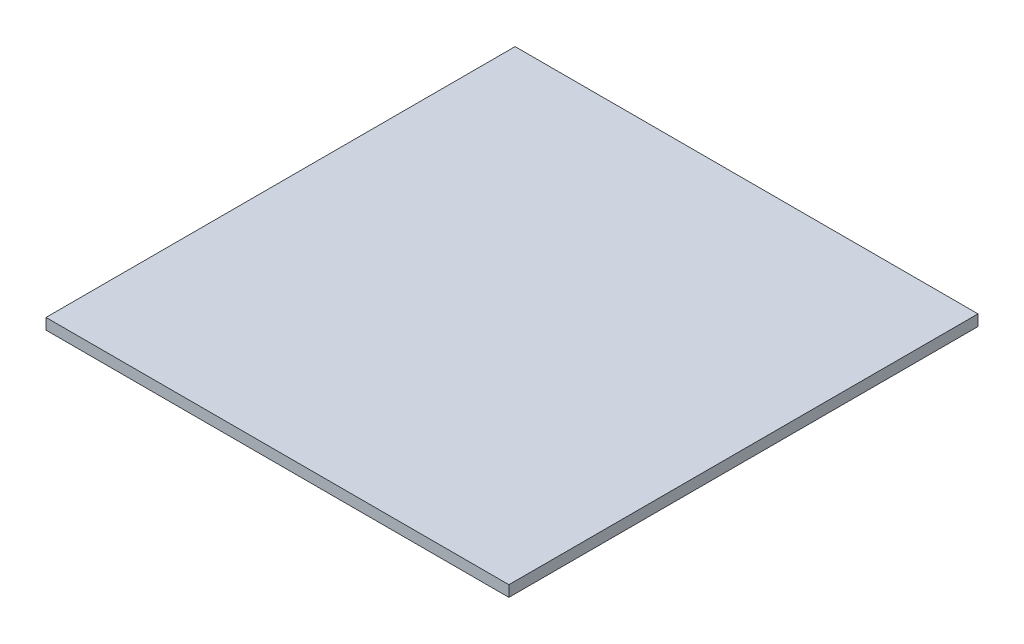
SolidWorks part; units mm, degrees
ref_plane "Plan de face" through (0, 0, 0) normal (0, 0, 1) x (1, 0, 0)
ref_plane "Plan de dessus" through (0, 0, 0) normal (0, 1, 0) x (1, 0, 0)
ref_plane "Plan de droite" through (0, 0, 0) normal (1, 0, 0) x (0, 0, -1)
sketch "Esquisse1" plane through (0, 0, 0) normal (0, 1, 0) x (1, 0, 0)
  line L0 (0, 0) -> (78.5, 0)
  line L1 (78.5, 0) -> (78.5, 79.55)
  line L2 (78.5, 79.55) -> (0, 79.55)
  line L3 (0, 79.55) -> (0, 0)
extrude "Boss.-Extru.1" add sketch "Esquisse1" along normal blind 1.87
